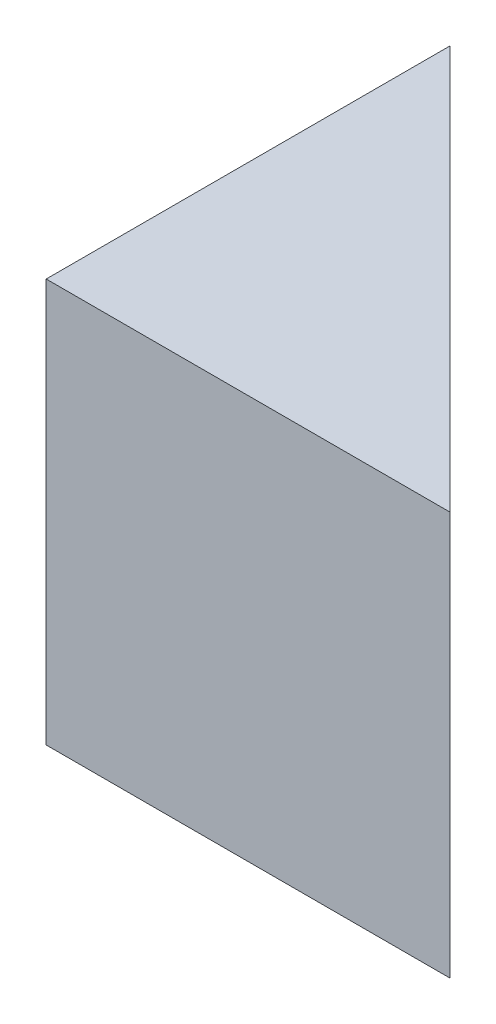
SolidWorks part; units mm, degrees
ref_plane "前视基准面" through (0, 0, 0) normal (0, 0, 1) x (1, 0, 0)
ref_plane "上视基准面" through (0, 0, 0) normal (0, 1, 0) x (1, 0, 0)
ref_plane "右视基准面" through (0, 0, 0) normal (1, 0, 0) x (0, 0, -1)
sketch "草图1" plane through (0, 0, 0) normal (0, 1, 0) x (1, 0, 0)
  line L1 (-7.5, 7.5) -> (7.5, 7.5)
  line L2 (-7.5, 7.5) -> (-7.5, -7.5)
  line L3 (-7.5, -7.5) -> (7.5, -7.5)
  line L4 (7.5, 7.5) -> (7.5, -7.5)
  line L5 (-7.5, 7.5) -> (7.5, -7.5) construction
  line L6 (-7.5, -7.5) -> (7.5, 7.5) construction
  point P0 (0, 0)
  dimension "D1" = 15
  dimension "D2" = 15
extrude "凸台-拉伸1" add sketch "草图1" along normal blind 15
sketch "草图2" plane through (0, 15, 0) normal (0, 1, 0) x (1, 0, 0)
  line L0 (-7.5, 7.5) -> (7.5, -7.5)
  line L1 (7.5, -7.5) -> (7.5, 7.5)
  line L2 (7.5, 7.5) -> (-7.5, 7.5)
extrude "切除-拉伸1" cut sketch "草图2" against normal through all and the other way through all
sketch "草图3" plane through (0, 0, 0) normal (0.7071, 0, -0.7071) x (-0.7071, 0, -0.7071)
  point P6 (0, 10)
sketch "草图4" plane through (0, 0, 0) normal (0.7071, 0, -0.7071) x (-0.7071, 0, -0.7071)
  line L0 (0, 15) -> (0, 0) construction
  point P4 (0, 7.5)
